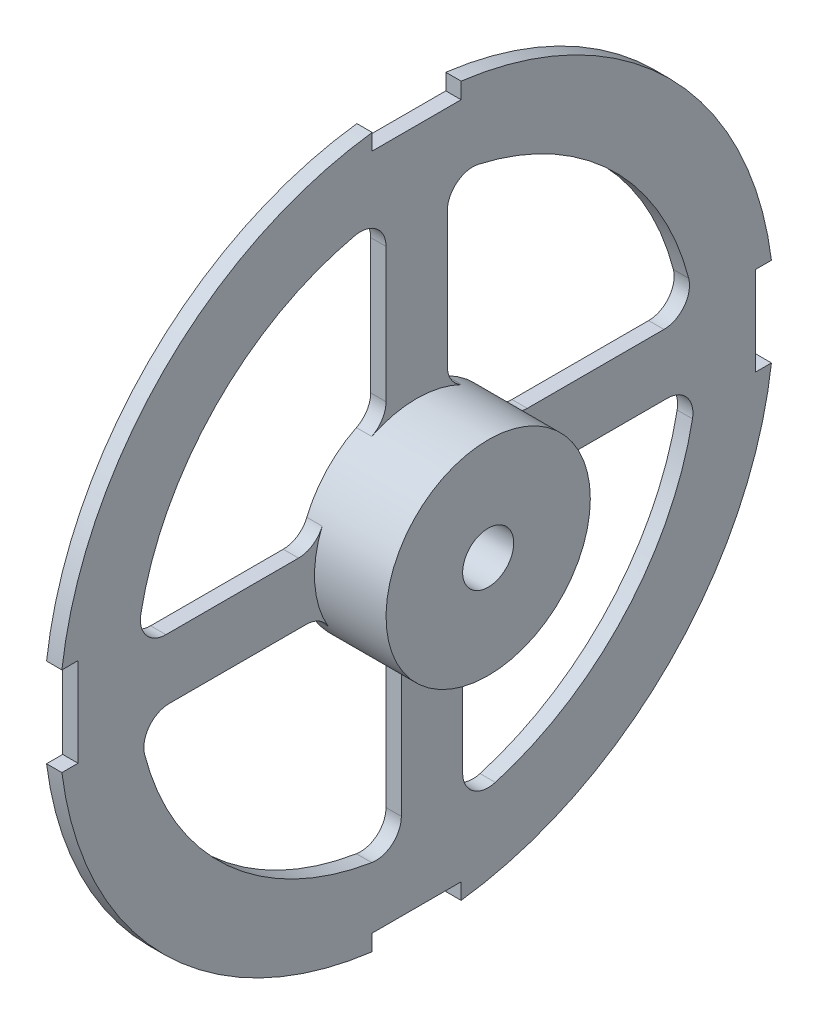
SolidWorks part; units mm, degrees
material "AISI 304"
ref_plane "Front Plane" through (0, 0, 0) normal (0, 0, 1) x (1, 0, 0)
ref_plane "Top Plane" through (0, 0, 0) normal (0, 1, 0) x (1, 0, 0)
ref_plane "Right Plane" through (0, 0, 0) normal (1, 0, 0) x (0, 0, -1)
sketch "Sketch1" plane through (0, 0, 0) normal (1, 0, 0) x (0, 0, -1)
  line L5 (0, 0) -> (0, 35) construction
  line L22 (-34.7286, 4.35) -> (-33.15, 4.35)
  line L23 (-33.15, 4.35) -> (-33.15, -4.35)
  line L47 (-34.7286, -4.35) -> (-33.15, -4.35)
  line L55 (-4.35, -34.7286) -> (-4.35, -33.15)
  line L56 (-4.35, -33.15) -> (4.35, -33.15)
  line L57 (4.35, -34.7286) -> (4.35, -33.15)
  line L61 (4.35, 34.7286) -> (4.35, 33.15)
  line L62 (4.35, 33.15) -> (-4.35, 33.15)
  line L63 (-4.35, 34.7286) -> (-4.35, 33.15)
  line L64 (34.7286, -4.35) -> (33.15, -4.35)
  line L65 (33.15, -4.35) -> (33.15, 4.35)
  line L66 (34.7286, 4.35) -> (33.15, 4.35)
  line L67 (9.2702, 3.75) -> (27.2431, 3.75)
  line L69 (-3, 9.5394) -> (-3, 27.3359)
  line L74 (3, 9.5394) -> (3, 27.3359)
  line L77 (9.7436, -2.25) -> (27.4078, -2.25)
  line L78 (4.5, -8.9303) -> (4.5, -27.1293)
  line L79 (-1.5, -9.8869) -> (-1.5, -27.4591)
  line L80 (-9.2702, -3.75) -> (-27.2431, -3.75)
  line L81 (-9.7436, 2.25) -> (-27.4078, 2.25)
  circle A1 centre (0, 0) radius 2.5
  circle A2 centre (0, 0) radius 40 construction
  arc A7 (4.35, -34.7286) -> (34.7286, -4.35) centre (0, 0) ccw
  arc A8 (34.7286, 4.35) -> (4.35, 34.7286) centre (0, 0) ccw
  arc A9 (-4.35, 34.7286) -> (-34.7286, 4.35) centre (0, 0) ccw
  arc A10 (-34.7286, -4.35) -> (-4.35, -34.7286) centre (0, 0) ccw
  arc A11 (27.2431, 3.75) -> (3, 27.3359) centre (0, 0) ccw
  arc A12 (-3, 9.5394) -> (-9.7436, 2.25) centre (0, 0) ccw
  arc A13 (9.2702, 3.75) -> (3, 9.5394) centre (0, 0) ccw
  arc A14 (4.5, -8.9303) -> (9.7436, -2.25) centre (0, 0) ccw
  arc A15 (4.5, -27.1293) -> (27.4078, -2.25) centre (0, 0) ccw
  arc A16 (-3, 27.3359) -> (-27.4078, 2.25) centre (0, 0) ccw
  arc A17 (-27.2431, -3.75) -> (-1.5, -27.4591) centre (0, 0) ccw
  arc A18 (-9.2702, -3.75) -> (-1.5, -9.8869) centre (0, 0) ccw
  point P8 (0, 18.6707)
  point P27 (0, 0)
  point P31 (0, 0)
  point P38 (0, 0)
  point P52 (0.75, 0)
  dimension "D6" = 5
  dimension "D7" = 3
  dimension "D5" = 80
  dimension "D1" = 70
  dimension "D8" = 55
  dimension "D9" = 20
  dimension "D2" = 4
  dimension "D3" = 8.7
  dimension "D4" = 4.35
  dimension "D10" = 6
  dimension "D11" = 4
extrude "Boss-Extrude3" add sketch "Sketch1" along normal blind 1.5
fillet "Fillet1" radius 2.5 16 edges at (0.75, -2.25, -27.4078) (0.75, -27.1293, -4.5) (0.75, -27.4591, 1.5) (0.75, -3.75, 27.2431) (0.75, -2.25, -9.7436) (0.75, -8.9303, -4.5) (0.75, -3.75, 9.2702) (0.75, -9.8869, 1.5) (0.75, 27.3359, 3) (0.75, 2.25, 27.4078) (0.75, 2.25, 9.7436) (0.75, 9.5394, 3) (0.75, 9.5394, -3) (0.75, 3.75, -9.2702) (0.75, 3.75, -27.2431) (0.75, 27.3359, -3)
sketch "Sketch3" plane through (1.5, 0, 0) normal (1, 0, 0) x (0, 0, -1)
  circle A0 centre (0, 0) radius 10
  circle A1 centre (0, 0) radius 2.5
  dimension "D1" = 5
extrude "Boss-Extrude4" add sketch "Sketch3" along normal blind 7
